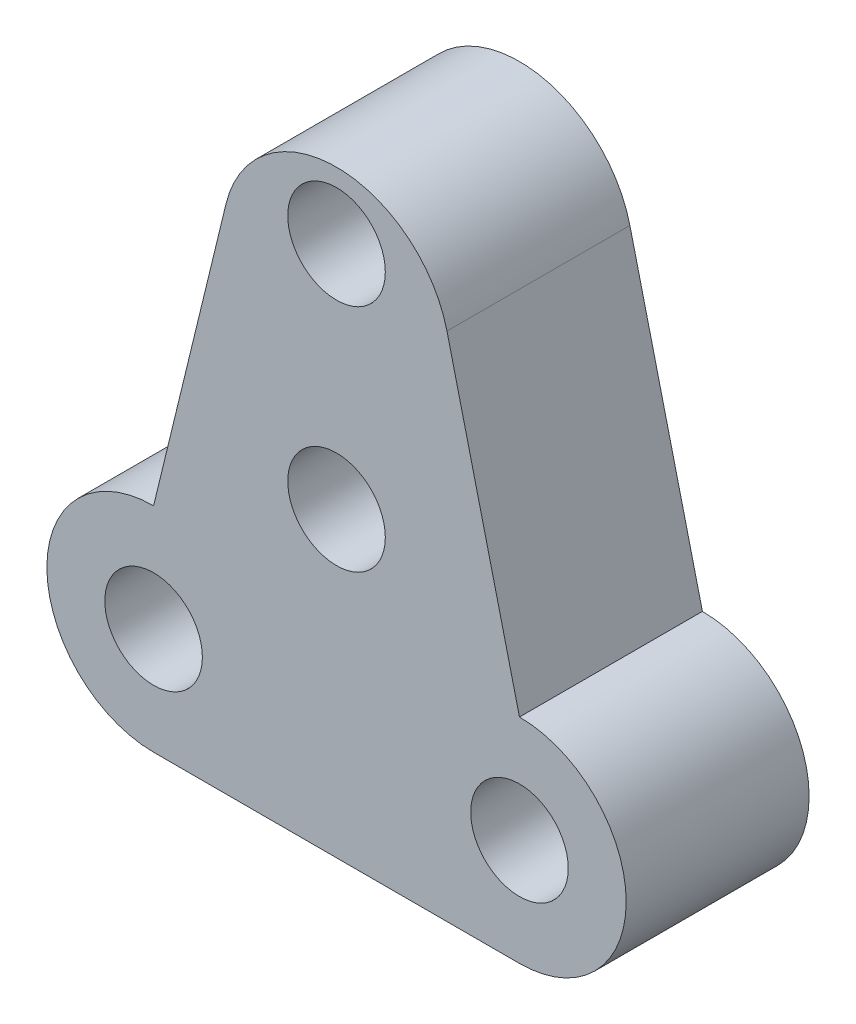
SolidWorks part; units mm, degrees
ref_plane "Alzado" through (0, 0, 0) normal (0, 0, 1) x (1, 0, 0)
ref_plane "Planta" through (0, 0, 0) normal (0, 1, 0) x (1, 0, 0)
ref_plane "Vista lateral" through (0, 0, 0) normal (1, 0, 0) x (0, 0, -1)
sketch "Croquis1" plane through (0, 0, 0) normal (0, 0, 1) x (1, 0, 0)
  line L0 (-6, 0) -> (6, 0)
  line L1 (0, 0) -> (0, 19.9239) construction
  line L2 (6, 7) -> (4, 15.22)
  line L3 (-6, 7) -> (-4, 15.22)
  line L4 (-4, 15.22) -> (-2.9294, 19.62)
  line L5 (-2.9294, 19.62) -> (2.9294, 19.62)
  line L6 (2.9294, 19.62) -> (4, 15.22)
  arc A0 (-6, 0) -> (-6, 7) centre (-6, 3.5) cw
  arc A1 (6, 0) -> (6, 7) centre (6, 3.5) ccw
  circle A3 centre (6, 3.5) radius 1.6
  circle A4 centre (-6, 3.5) radius 1.6
  circle A5 centre (0, 17.44) radius 1.6
  circle A6 centre (0, 9.9) radius 1.6
  point P4 (0, 0)
  dimension "D2" = 3.5
  dimension "D6" = 3.2
  dimension "D7" = 3.2
  dimension "D1" = 12
  dimension "D3" = 2.18
  dimension "D4" = 8.22
  dimension "D5" = 4
  dimension "D8" = 4.4
  dimension "D9" = 9.9
extrude "Saliente-Extruir1" add sketch "Croquis1" along normal blind 6
fillet "Redondeo1" radius 3.7277 4 edges at (-2.9294, 19.62, 3) (2.9294, 19.62, 3) (0, 19.62, 6) (0, 19.62, 0)
